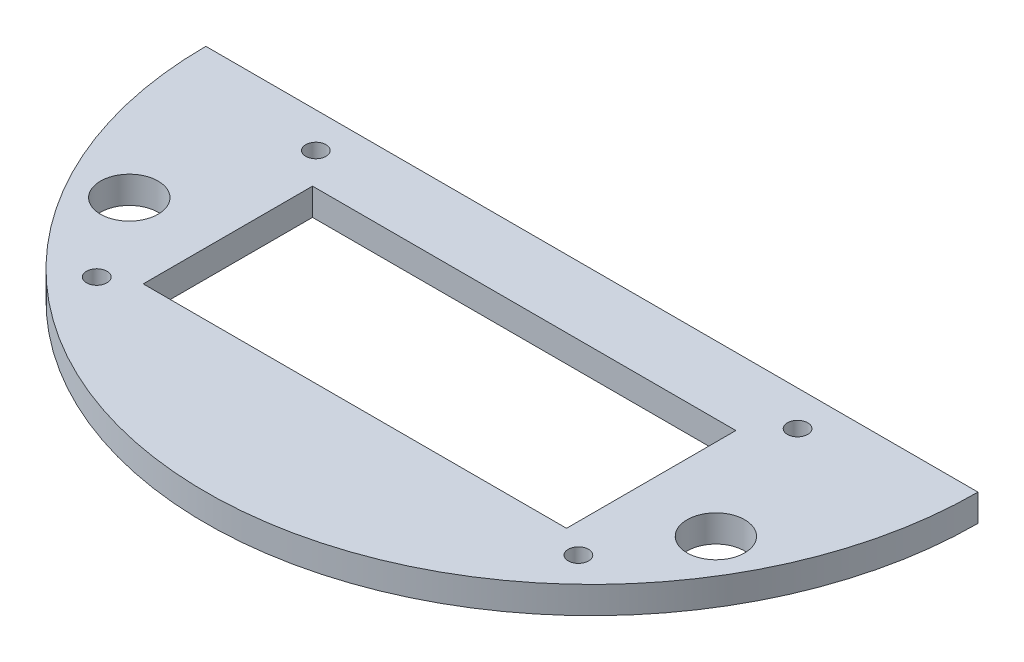
SolidWorks part; units mm, degrees
ref_plane "Plan de face" through (0, 0, 0) normal (0, 0, 1) x (1, 0, 0)
ref_plane "Plan de dessus" through (0, 0, 0) normal (0, 1, 0) x (1, 0, 0)
ref_plane "Plan de droite" through (0, 0, 0) normal (1, 0, 0) x (0, 0, -1)
sketch "Esquisse1" plane through (0, 0, 0) normal (0, 1, 0) x (1, 0, 0)
  line L0 (-57, 0) -> (57, 0)
  line L1 (0, -22.5) -> (0, 0) construction
  line L2 (-31.25, -10) -> (31.25, -10)
  line L3 (-31.25, -10) -> (-31.25, -35)
  line L4 (-31.25, -35) -> (31.25, -35)
  line L5 (31.25, -10) -> (31.25, -35)
  line L6 (-31.25, -10) -> (31.25, -35) construction
  line L7 (-31.25, -35) -> (31.25, -10) construction
  line L8 (-43.3013, -25) -> (0, 0) construction
  line L9 (0, 0) -> (43.3013, -25) construction
  line L10 (43.3013, -25) -> (-43.3013, -25) construction
  line L12 (-31.25, -35) -> (0.75, -35) construction
  line L13 (-31.25, -35) -> (-31.25, -43.6) construction
  line L14 (-31.25, -43.6) -> (0.75, -43.6) construction
  line L15 (0.75, -35) -> (0.75, -43.6) construction
  line L16 (-31.25, -35) -> (0.75, -43.6) construction
  line L17 (-31.25, -43.6) -> (0.75, -35) construction
  arc A0 (-57, 0) -> (57, 0) centre (0, 0) ccw
  circle A1 centre (-43.3013, -25) radius 4.25
  circle A2 centre (43.3013, -25) radius 4.25
  point P4 (0, -22.5)
  point P16 (-15.25, -39.3)
  point P22 (0, 0)
  dimension "D1" = 57
  dimension "D6" = 8.5
  dimension "D2" = 25
  dimension "D3" = 62.5
  dimension "D4" = 50
  dimension "D5" = 120
  dimension "D7" = 8.6
  dimension "D8" = 32
  dimension "D9" = 22.5
extrude "Boss.-Extru.1" add sketch "Esquisse1" along normal blind 4
sketch "Esquisse2" plane through (0, 4, 0) normal (0, 1, 0) x (1, 0, 0)
  line L0 (0, -21.3765) -> (0, 0) construction
  line L1 (35.5571, -37.5546) -> (-35.5571, -37.5546) construction
  line L2 (35.5571, -37.5546) -> (35.5571, -5.1985) construction
  line L3 (35.5571, -5.1985) -> (-35.5571, -5.1985) construction
  line L4 (-35.5571, -37.5546) -> (-35.5571, -5.1985) construction
  line L5 (35.5571, -37.5546) -> (-35.5571, -5.1985) construction
  line L6 (35.5571, -5.1985) -> (-35.5571, -37.5546) construction
  circle A0 centre (-35.5571, -37.5546) radius 5 construction
  circle A1 centre (-35.5571, -37.5546) radius 1.5
  circle A2 centre (-35.5571, -5.1985) radius 5 construction
  circle A3 centre (-35.5571, -5.1985) radius 1.5
  circle A4 centre (35.5571, -5.1985) radius 1.5
  circle A5 centre (35.5571, -37.5546) radius 1.5
  point P0 (0, -21.3765)
  dimension "D1" = 10
  dimension "D2" = 3
  dimension "D3" = 3
  dimension "D4" = 10
  dimension "D5" = 3
  dimension "D6" = 3
  dimension "D7" = 5.1985
  dimension "D8" = 37.5546
  dimension "D9" = 35.5571
extrude "Enlèv. mat.-Extru.1" cut sketch "Esquisse2" against normal through all
